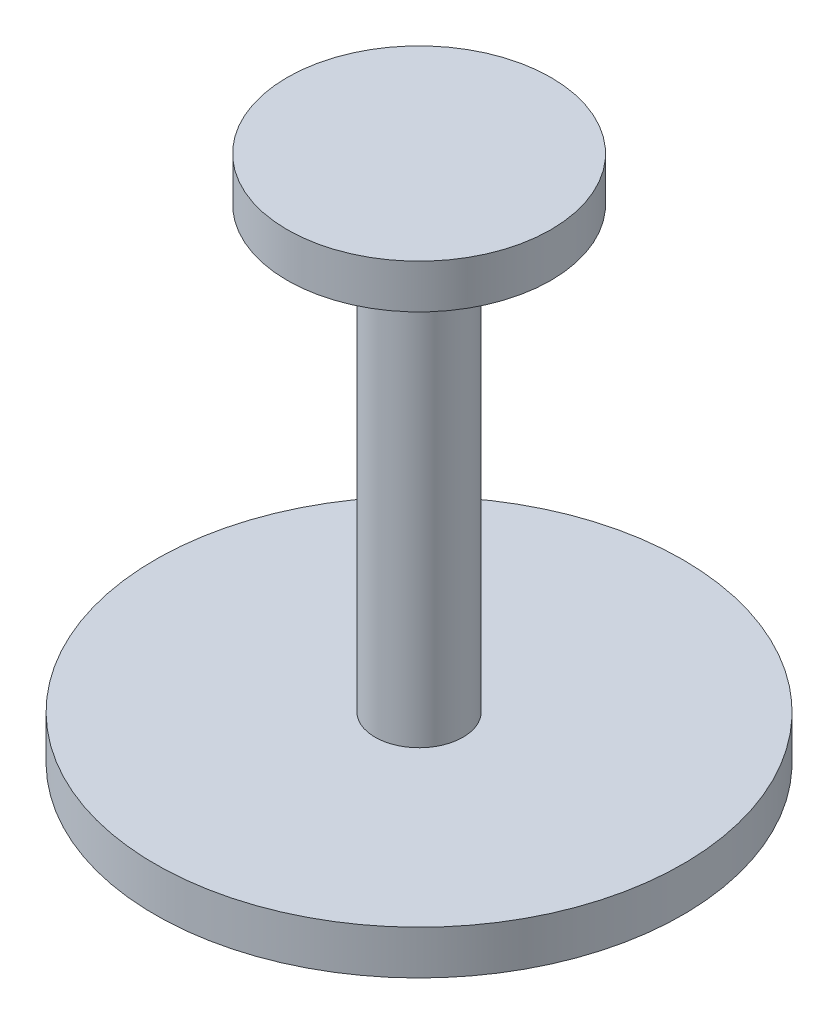
SolidWorks part; units mm, degrees
ref_plane "Front Plane" through (0, 0, 0) normal (0, 0, 1) x (1, 0, 0)
ref_plane "Top Plane" through (0, 0, 0) normal (0, 1, 0) x (1, 0, 0)
ref_plane "Right Plane" through (0, 0, 0) normal (1, 0, 0) x (0, 0, -1)
sketch "Sketch2" plane through (0, 0, 0) normal (0, 0, 1) x (1, 0, 0)
  line L0 (0, 0) -> (0, 76.2)
  line L1 (0, 76.2) -> (19.05, 76.2)
  line L2 (19.05, 76.2) -> (19.05, 69.85)
  line L3 (19.05, 69.85) -> (6.35, 69.85)
  line L4 (6.35, 69.85) -> (6.35, 6.35)
  line L5 (6.35, 6.35) -> (38.1, 6.35)
  line L6 (38.1, 6.35) -> (38.1, 0)
  line L7 (38.1, 0) -> (0, 0)
  dimension "D1" = 76.2
  dimension "D2" = 38.1
  dimension "D3" = 6.35
  dimension "D4" = 6.35
  dimension "D5" = 19.05
  dimension "D6" = 6.35
revolve "Revolve1" add sketch "Sketch2" angle 360 about L0
